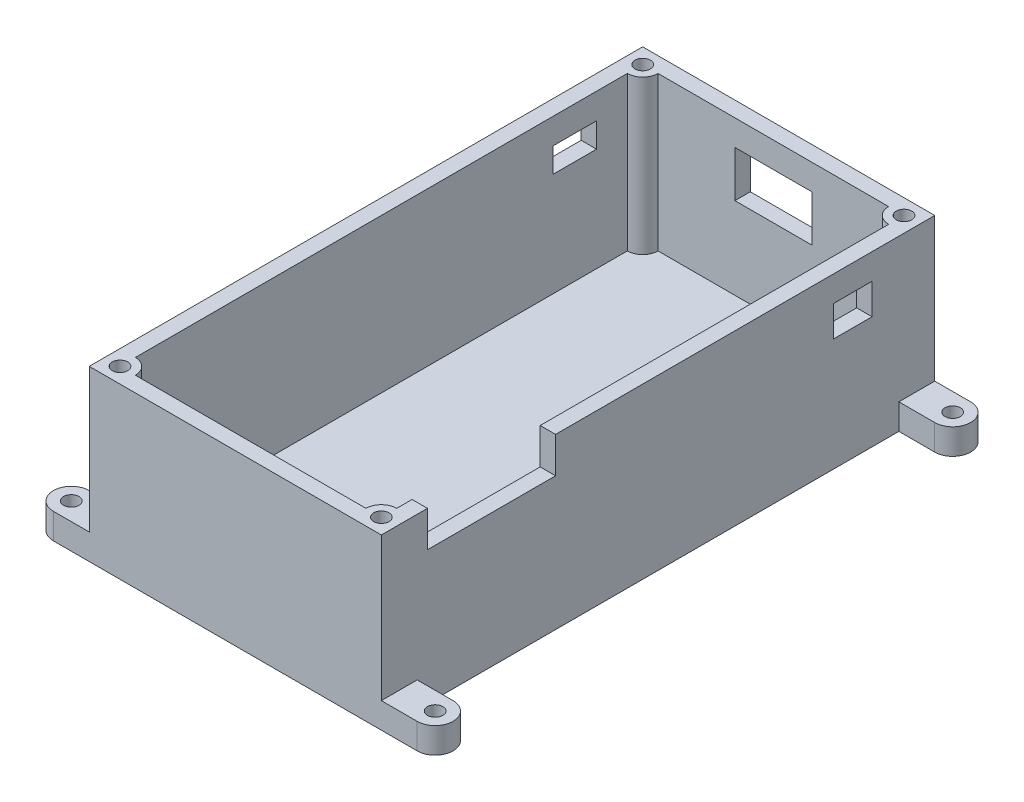
SolidWorks part; units mm, degrees
ref_plane "Alzado" through (0, 0, 0) normal (0, 0, 1) x (1, 0, 0)
ref_plane "Planta" through (0, 0, 0) normal (0, 1, 0) x (1, 0, 0)
ref_plane "Vista lateral" through (0, 0, 0) normal (1, 0, 0) x (0, 0, -1)
sketch "Croquis1" plane through (0, 0, 0) normal (0, 1, 0) x (1, 0, 0)
  line L1 (-25.5, 51) -> (25.5, 51)
  line L2 (-25.5, 51) -> (-25.5, -51)
  line L3 (-25.5, -51) -> (25.5, -51)
  line L4 (25.5, 51) -> (25.5, -51)
  point P4 (0, 51)
  point P6 (-25.5, 0)
  dimension "D1" = 102
  dimension "D2" = 51
extrude "Saliente-Extruir1" add sketch "Croquis1" along normal blind 30
shell "Vaciado1" thickness 3
sketch "Croquis5" plane through (0, -3, 0) normal (0, -1, 0) x (1, 0, 0)
  line L0 (28.5, 54) -> (35.5, 54)
  line L1 (28.5, 54) -> (28.5, 47)
  line L2 (28.5, 54) -> (28.5, -54) construction
  line L3 (28.5, 47) -> (35.5, 47)
  line L4 (-28.5, 54) -> (-35.5, 54)
  line L5 (-28.5, 54) -> (-28.5, 47)
  line L6 (-28.5, -54) -> (-28.5, 54) construction
  line L7 (-28.5, 47) -> (-35.5, 47)
  line L8 (-28.5, -54) -> (-35.5, -54)
  line L9 (-28.5, -54) -> (-28.5, -47)
  line L10 (-28.5, -47) -> (-35.5, -47)
  line L11 (28.5, -54) -> (35.5, -54)
  line L12 (28.5, -54) -> (28.5, -47)
  line L13 (28.5, -47) -> (35.5, -47)
  arc A0 (35.5, 47) -> (35.5, 54) centre (35.5, 50.5) ccw
  circle A1 centre (35.5, 50.5) radius 1.5
  arc A2 (-35.5, 54) -> (-35.5, 47) centre (-35.5, 50.5) ccw
  circle A3 centre (-35.5, 50.5) radius 1.5
  arc A4 (-35.5, -47) -> (-35.5, -54) centre (-35.5, -50.5) ccw
  circle A5 centre (-35.5, -50.5) radius 1.5
  arc A6 (35.5, -54) -> (35.5, -47) centre (35.5, -50.5) ccw
  circle A7 centre (35.5, -50.5) radius 1.5
  dimension "D3" = 7
  dimension "D4" = 3
  dimension "D7" = 7
  dimension "D8" = 3
  dimension "D11" = 7
  dimension "D12" = 3
  dimension "D15" = 7
  dimension "D16" = 3
  dimension "D1" = 7
  dimension "D2" = 7
  dimension "D5" = 7
  dimension "D6" = 7
  dimension "D9" = 7
  dimension "D10" = 7
  dimension "D13" = 7
  dimension "D14" = 7
extrude "Saliente-Extruir2" add sketch "Croquis5" against normal blind 5
sketch "Croquis8" plane through (0, 0, 0) normal (0, 1, 0) x (1, 0, 0)
  circle A1 centre (-25.5, 51) radius 3
  circle A3 centre (25.5, 51) radius 3
  circle A4 centre (25.5, -51) radius 3
  circle A5 centre (-25.5, -51) radius 3
  dimension "D1" = 6
  dimension "D2" = 6
  dimension "D3" = 6
  dimension "D4" = 6
extrude "Saliente-Extruir3" add sketch "Croquis8" along normal blind 30
sketch "Croquis10" plane through (0, 30, 0) normal (0, 1, 0) x (1, 0, 0)
  circle A0 centre (-25.5, 51) radius 1.5
  arc A1 (-25.5, 48) -> (-22.5, 51) centre (-25.5, 51) ccw construction
  circle A2 centre (25.5, 51) radius 1.5
  arc A3 (22.5, 51) -> (25.5, 48) centre (25.5, 51) ccw construction
  circle A4 centre (-25.5, -51) radius 1.5
  arc A5 (-22.5, -51) -> (-25.5, -48) centre (-25.5, -51) ccw construction
  circle A6 centre (25.5, -51) radius 1.5
  arc A7 (25.5, -48) -> (22.5, -51) centre (25.5, -51) ccw construction
  dimension "D1" = 3
  dimension "D2" = 3
  dimension "D3" = 3
  dimension "D4" = 3
extrude "Cortar-Extruir1" cut sketch "Croquis10" against normal blind 25
sketch "Croquis14" plane through (28.5, 0, 0) normal (1, 0, 0) x (0, 0, -1)
  line L0 (-54, 30) -> (54, 30) construction
  line L1 (-45, 30) -> (-20, 30)
  line L2 (-45, 30) -> (-45, 23)
  line L3 (-45, 23) -> (-20, 23)
  line L4 (-20, 30) -> (-20, 23)
  line L5 (-54, 30) -> (-54, 2) construction
  dimension "D1" = 9
  dimension "D2" = 7
  dimension "D3" = 25
extrude "Cortar-Extruir3" cut sketch "Croquis14" against normal blind 3
sketch "Croquis15" plane through (-28.5, 0, 0) normal (-1, 0, 0) x (0, 0, 1)
  line L0 (-54, 30) -> (54, 30) construction
  line L1 (-42, 25) -> (-33.5, 25)
  line L2 (-42, 25) -> (-42, 20.2)
  line L3 (-42, 20.2) -> (-33.5, 20.2)
  line L4 (-33.5, 25) -> (-33.5, 20.2)
  line L5 (-54, 30) -> (-54, 2) construction
  dimension "D1" = 5
  dimension "D2" = 12
  dimension "D3" = 8.5
  dimension "D4" = 4.8
extrude "Cortar-Extruir4" cut sketch "Croquis15" against normal blind 3
sketch "Croquis16" plane through (28.5, 0, 0) normal (1, 0, 0) x (0, 0, -1)
  line L0 (-20, 30) -> (54, 30) construction
  line L1 (34.28, 25) -> (41.76, 25)
  line L2 (34.28, 25) -> (34.28, 19)
  line L3 (34.28, 19) -> (41.76, 19)
  line L4 (41.76, 25) -> (41.76, 19)
  line L5 (54, 30) -> (54, 2) construction
  dimension "D1" = 5
  dimension "D2" = 12.24
  dimension "D3" = 7.48
  dimension "D4" = 6
extrude "Cortar-Extruir5" cut sketch "Croquis16" against normal blind 3
sketch "Croquis17" plane through (0, -3, 0) normal (0, -1, 0) x (1, 0, 0)
  line L0 (35.5, -54) -> (-35.5, -54) construction
  circle A0 centre (0, -42) radius 2.5
  point P5 (0, -54)
  dimension "D1" = 5
  dimension "D2" = 12
extrude "Cortar-Extruir6" cut sketch "Croquis17" against normal blind 3
sketch "Croquis18" plane through (0, 0, -54) normal (0, 0, -1) x (-1, 0, 0)
  line L1 (-7.5, 25) -> (7.5, 25)
  line L2 (-7.5, 25) -> (-7.5, 16)
  line L3 (-7.5, 16) -> (7.5, 16)
  line L4 (7.5, 25) -> (7.5, 16)
  line L5 (28.5, 30) -> (28.5, 2) construction
  line L6 (-28.5, 30) -> (28.5, 30) construction
  dimension "D1" = 5
  dimension "D2" = 21
  dimension "D3" = 15
  dimension "D4" = 9
extrude "Cortar-Extruir7" cut sketch "Croquis18" against normal up to vertex (54 mm away) up to point (0, 0, 0)
